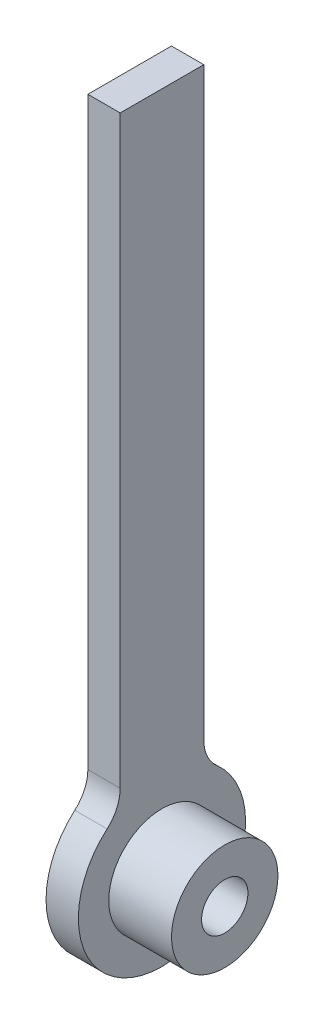
SolidWorks part; units mm, degrees
ref_plane "Front Plane" through (0, 0, 0) normal (0, 0, 1) x (1, 0, 0)
ref_plane "Top Plane" through (0, 0, 0) normal (0, 1, 0) x (1, 0, 0)
ref_plane "Right Plane" through (0, 0, 0) normal (1, 0, 0) x (0, 0, -1)
sketch "Sketch2" plane through (0, 0, 0) normal (1, 0, 0) x (0, 0, -1)
  line L1 (0, 0) -> (44, 0)
  line L2 (0, 0) -> (0, 200)
  line L3 (0, 200) -> (44, 200)
  line L4 (44, 0) -> (44, 200)
  dimension "D1" = 44
  dimension "D2" = 200
extrude "Boss-Extrude2" add sketch "Sketch2" along normal blind 8.5
sketch "Sketch4" plane through (0, 0, 0) normal (1, 0, 0) x (0, 0, -1)
  line L0 (0, 0) -> (44, 0) construction
  circle A0 centre (22, 22) radius 11.04
  point P6 (22, 0)
  dimension "D1" = 22
  dimension "D3" = 22.08
extrude "Cut-Extrude1" cut sketch "Sketch4" along normal offset from surface (7.5 mm away) 1 up to face at (8.5, 100, -22)
sketch "Sketch5" plane through (8.5, 0, 0) normal (1, 0, 0) x (0, 0, -1)
  line L0 (11, 200) -> (11, 46.1454)
  line L1 (44, 200) -> (0, 200) construction
  line L3 (22, 200) -> (22, 0) construction
  line L4 (11, 200) -> (33, 200)
  line L5 (33, 200) -> (33, 46.1454)
  line L6 (0, 0) -> (44, 0) construction
  arc A0 (11, 46.1454) -> (7.5625, 38.6) centre (1, 46.1454) cw
  arc A1 (7.5625, 38.6) -> (36.4375, 38.6) centre (22, 22) ccw
  arc A2 (33, 46.1454) -> (36.4375, 38.6) centre (43, 46.1454) ccw
  circle A3 centre (22, 22) radius 8
  dimension "D2" = 10
  dimension "D3" = 16
  dimension "D1" = 11
extrude "Cut-Extrude2" cut sketch "Sketch5" against normal blind 10 flip side to cut
sketch "Sketch6" plane through (8.5, 0, 0) normal (1, 0, 0) x (0, 0, -1)
  circle A0 centre (22, 22) radius 14
extrude "Boss-Extrude3" add sketch "Sketch6" along normal blind 16.51
sketch "Sketch8" plane through (25.01, 0, 0) normal (1, 0, 0) x (0, 0, -1)
  circle A0 centre (22, 22) radius 6.096
extrude "Cut-Extrude4" cut sketch "Sketch8" against normal blind 16.51
